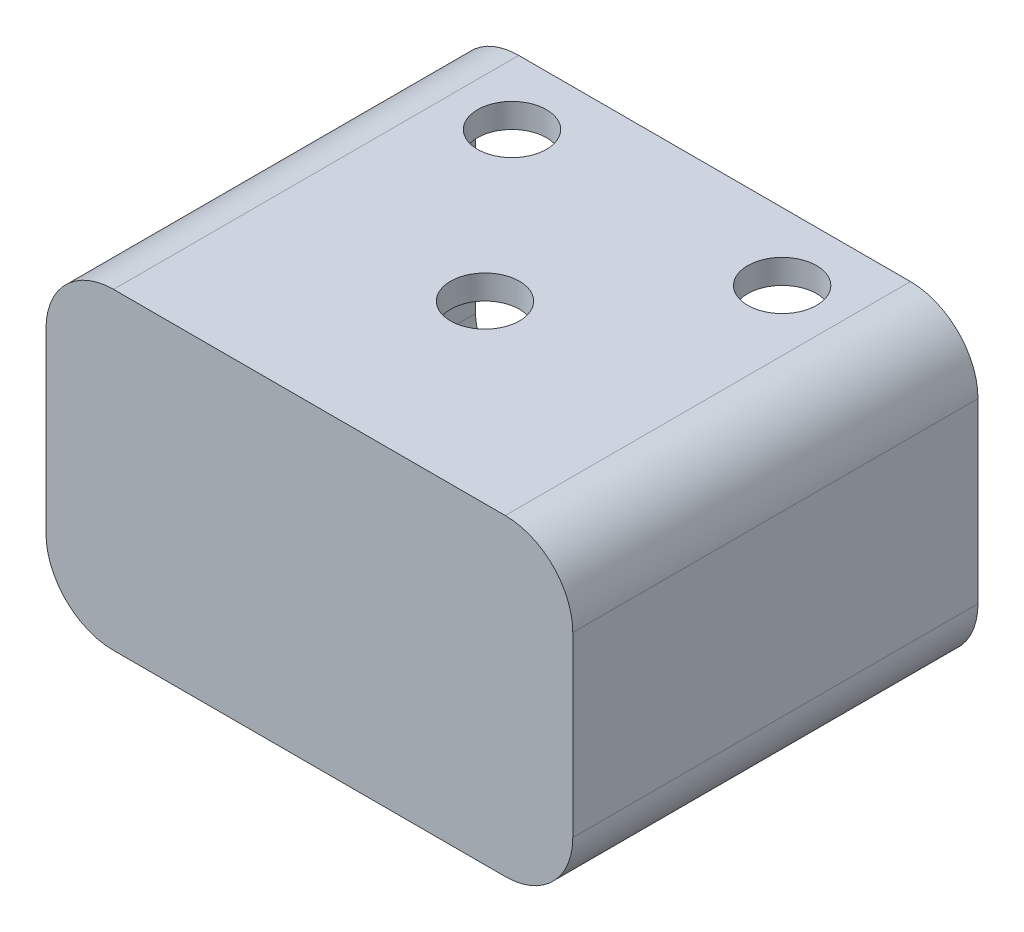
SolidWorks part; units mm, degrees
ref_plane "Front Plane" through (0, 0, 0) normal (0, 0, 1) x (1, 0, 0)
ref_plane "Top Plane" through (0, 0, 0) normal (0, 1, 0) x (1, 0, 0)
ref_plane "Right Plane" through (0, 0, 0) normal (1, 0, 0) x (0, 0, -1)
sketch "Sketch4" plane through (0, 0, 304.8) normal (0, 0, 1) x (1, 0, 0)
  line L8 (35.5, 1.5) -> (35.5, 14.65)
  line L9 (30.5, 19.65) -> (1.5, 19.65)
  line L10 (-3.5, 14.65) -> (-3.5, 1.5)
  line L11 (1.5, -3.5) -> (30.5, -3.5)
  line L12 (35.5, 1.5) -> (35.5, 14.65)
  line L13 (30.5, 19.65) -> (1.5, 19.65)
  line L14 (-3.5, 14.65) -> (-3.5, 1.5)
  line L15 (1.5, -3.5) -> (30.5, -3.5)
  arc A8 (35.5, 14.65) -> (30.5, 19.65) centre (30.5, 14.65) ccw
  arc A9 (1.5, 19.65) -> (-3.5, 14.65) centre (1.5, 14.65) ccw
  arc A10 (-3.5, 1.5) -> (1.5, -3.5) centre (1.5, 1.5) ccw
  arc A11 (30.5, -3.5) -> (35.5, 1.5) centre (30.5, 1.5) ccw
  arc A12 (35.5, 14.65) -> (30.5, 19.65) centre (30.5, 14.65) ccw
  arc A13 (1.5, 19.65) -> (-3.5, 14.65) centre (1.5, 14.65) ccw
  arc A14 (-3.5, 1.5) -> (1.5, -3.5) centre (1.5, 1.5) ccw
  arc A15 (30.5, -3.5) -> (35.5, 1.5) centre (30.5, 1.5) ccw
  dimension "D1" = 2
extrude "Boss-Extrude2" add sketch "Sketch4" along normal blind 5
sketch "Sketch6" plane through (0, 0, 304.8) normal (0, 0, -1) x (-1, 0, 0)
  line L8 (-1.5, 17.85) -> (-30.5, 17.85)
  line L9 (-33.7, 14.65) -> (-33.7, 1.5)
  line L10 (-30.5, -1.7) -> (-1.5, -1.7)
  line L11 (1.7, 1.5) -> (1.7, 14.65)
  line L12 (-1.5, 17.85) -> (-30.5, 17.85)
  line L13 (-33.7, 14.65) -> (-33.7, 1.5)
  line L14 (-30.5, -1.7) -> (-1.5, -1.7)
  line L15 (1.7, 1.5) -> (1.7, 14.65)
  line L16 (-30.5, -3.5) -> (-1.5, -3.5)
  line L17 (3.5, 1.5) -> (3.5, 14.65)
  line L18 (-1.5, 19.65) -> (-30.5, 19.65)
  line L19 (-35.5, 14.65) -> (-35.5, 1.5)
  line L20 (-30.5, -3.5) -> (-1.5, -3.5)
  line L21 (3.5, 1.5) -> (3.5, 14.65)
  line L22 (-1.5, 19.65) -> (-30.5, 19.65)
  line L23 (-35.5, 14.65) -> (-35.5, 1.5)
  arc A8 (-30.5, 17.85) -> (-33.7, 14.65) centre (-30.5, 14.65) ccw
  arc A9 (-33.7, 1.5) -> (-30.5, -1.7) centre (-30.5, 1.5) ccw
  arc A10 (-1.5, -1.7) -> (1.7, 1.5) centre (-1.5, 1.5) ccw
  arc A11 (1.7, 14.65) -> (-1.5, 17.85) centre (-1.5, 14.65) ccw
  arc A12 (-30.5, 17.85) -> (-33.7, 14.65) centre (-30.5, 14.65) ccw
  arc A13 (-33.7, 1.5) -> (-30.5, -1.7) centre (-30.5, 1.5) ccw
  arc A14 (-1.5, -1.7) -> (1.7, 1.5) centre (-1.5, 1.5) ccw
  arc A15 (1.7, 14.65) -> (-1.5, 17.85) centre (-1.5, 14.65) ccw
  arc A16 (-35.5, 1.5) -> (-30.5, -3.5) centre (-30.5, 1.5) ccw
  arc A17 (-1.5, -3.5) -> (3.5, 1.5) centre (-1.5, 1.5) ccw
  arc A18 (3.5, 14.65) -> (-1.5, 19.65) centre (-1.5, 14.65) ccw
  arc A19 (-30.5, 19.65) -> (-35.5, 14.65) centre (-30.5, 14.65) ccw
  arc A20 (-35.5, 1.5) -> (-30.5, -3.5) centre (-30.5, 1.5) ccw
  arc A21 (-1.5, -3.5) -> (3.5, 1.5) centre (-1.5, 1.5) ccw
  arc A22 (3.5, 14.65) -> (-1.5, 19.65) centre (-1.5, 14.65) ccw
  arc A23 (-30.5, 19.65) -> (-35.5, 14.65) centre (-30.5, 14.65) ccw
  dimension "D1" = 0.2
  dimension "D2" = 0
extrude "Boss-Extrude3" add sketch "Sketch6" along normal blind 25
sketch "Sketch7" plane through (0, 19.65, 0) normal (0, 1, 0) x (1, 0, 0)
  circle A0 centre (16, -296.8) radius 2.55 construction
  circle A1 centre (26, -284.8) radius 2.55 construction
  circle A2 centre (6, -284.8) radius 2.55 construction
  circle A3 centre (16, -296.8) radius 2.55
  circle A4 centre (26, -284.8) radius 2.55
  circle A5 centre (6, -284.8) radius 2.55
extrude "Cut-Extrude1" cut sketch "Sketch7" against normal through all
